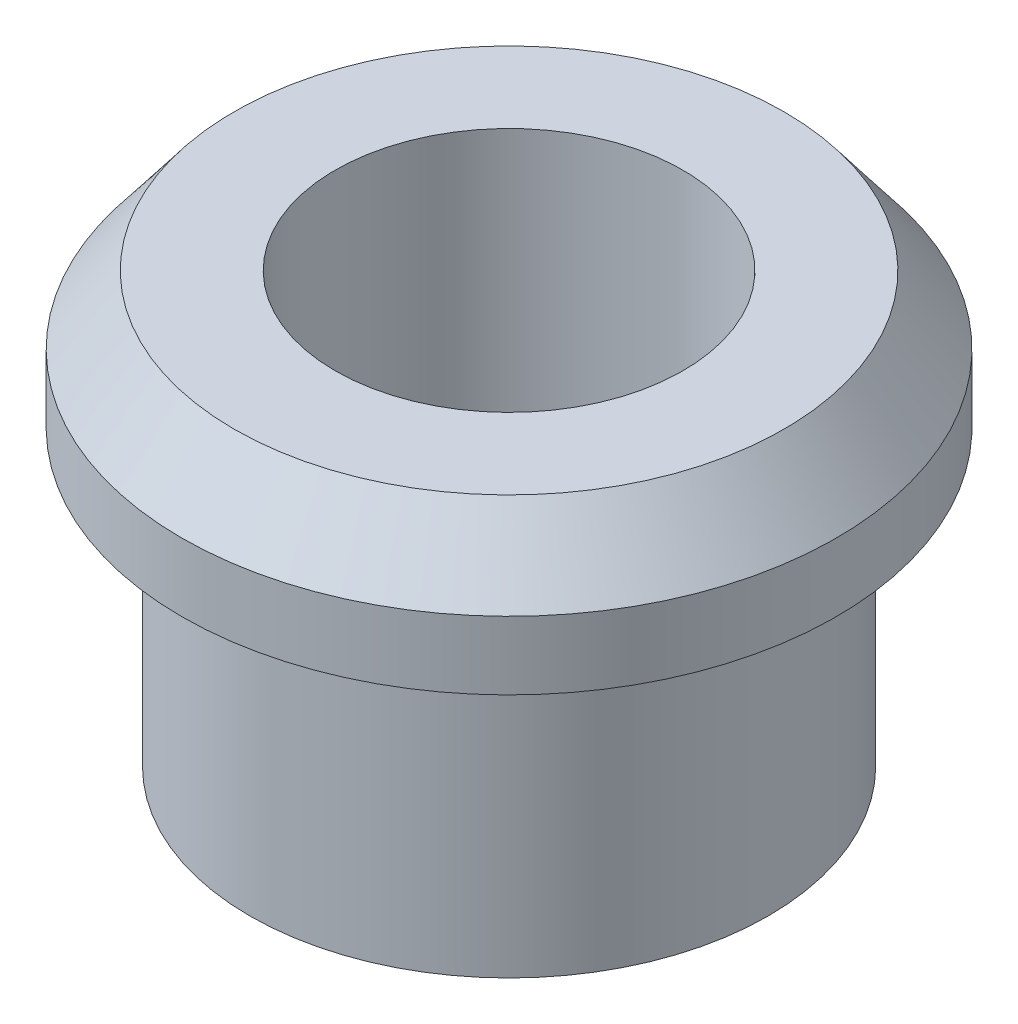
SolidWorks part; units mm, degrees
ref_plane "Front Plane" through (0, 0, 0) normal (0, 0, 1) x (1, 0, 0)
ref_plane "Top Plane" through (0, 0, 0) normal (0, 1, 0) x (1, 0, 0)
ref_plane "Right Plane" through (0, 0, 0) normal (1, 0, 0) x (0, 0, -1)
sketch "Sketch1" plane through (0, 0, 0) normal (0, 0, 1) x (1, 0, 0)
  line L1 (6.2865, -4.9157) -> (6.2865, 2.1963)
  line L2 (6.2865, 2.1963) -> (7.9375, 2.1963)
  line L3 (7.9375, 2.1963) -> (7.9375, 3.8473)
  line L4 (7.9375, 3.8473) -> (6.6675, 5.4983)
  line L5 (6.6675, 5.4983) -> (0, 5.4983)
  line L10 (0, 5.4983) -> (0, -4.9157)
  line L11 (0, -4.9157) -> (6.2865, -4.9157)
  dimension "D1" = 6.2865
  dimension "D2" = 7.112
  dimension "D3" = 1.651
  dimension "D4" = 1.651
  dimension "D5" = 6.6675
  dimension "D6" = 7.9375
revolve "Revolve1" add sketch "Sketch1" angle 360 about L10
sketch "Sketch4" plane through (0, 5.4983, 0) normal (0, 1, 0) x (1, 0, 0)
  point P0 (0, 0)
hole_wizard "3/8-24 Tapped Hole1" positions "Sketch4" profile "Sketch3" tap size "3/8-24" standard "ANSI Inch" end condition through all
sketch "Sketch3" plane through (0, 5.4983, 0) normal (1, 0, 0) x (0, 0, 1)
  line L0 (0, 0) -> (0, 10.414)
  line L1 (0, 10.414) -> (4.2164, 10.414)
  line L2 (4.2164, 10.414) -> (4.2164, 0)
  line L5 (4.2164, 0) -> (0, 0)
  line L11 (0, -6.35) -> (0, 107.95) construction
  dimension "Thru Tap Drill Dia." = 8.4328
  dimension "Thru Tap Drill Depth" = 10.414
cosmetic thread "Hole Thread1" parameters "D2"=9.525
